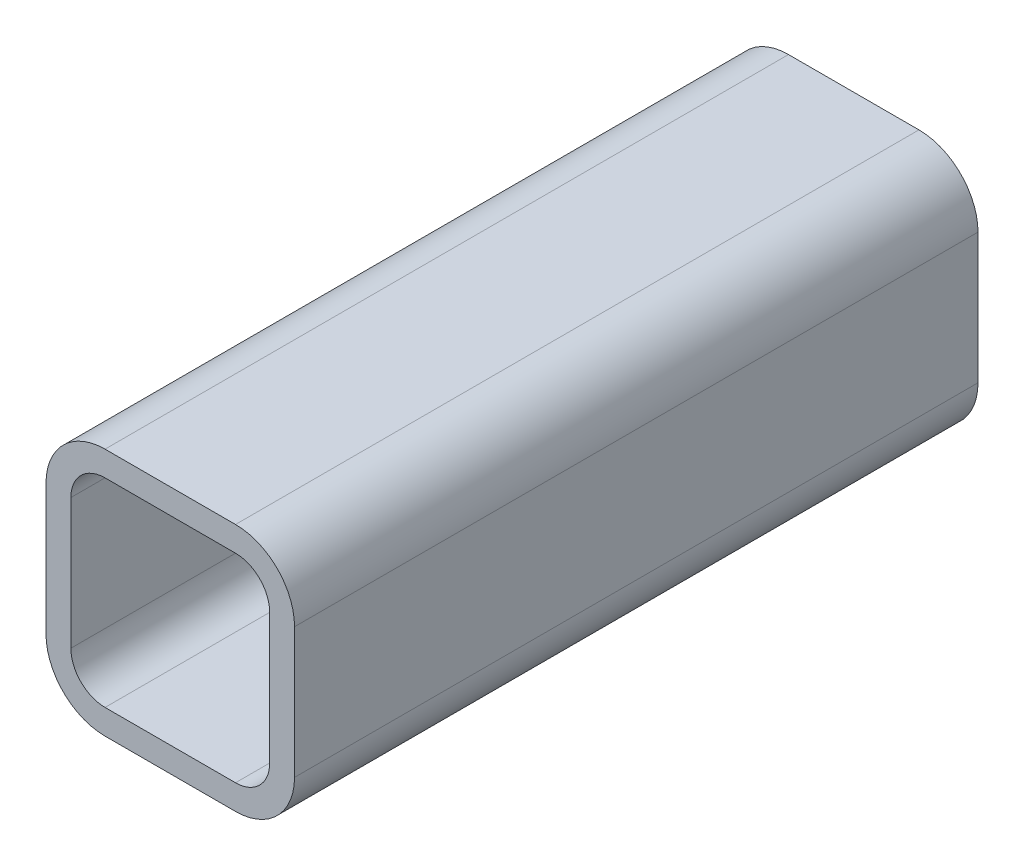
SolidWorks part; units mm, degrees
material "Q355"
ref_plane "前视基准面" through (0, 0, 0) normal (0, 0, 1) x (1, 0, 0)
ref_plane "上视基准面" through (0, 0, 0) normal (0, 1, 0) x (1, 0, 0)
ref_plane "右视基准面" through (0, 0, 0) normal (1, 0, 0) x (0, 0, -1)
sketch "草图1" plane through (0, 0, 0) normal (0, 0, 1) x (1, 0, 0)
  line L5 (0, 0) -> (0, 73.118) construction
  line L13 (0, 0) -> (96.1876, 0) construction
  line L14 (-32, 21) -> (-32, -21)
  line L15 (-21, 40) -> (21, 40)
  line L16 (-40, 21) -> (-40, -21)
  line L17 (-21, -40) -> (21, -40)
  line L18 (40, 21) -> (40, -21)
  line L19 (-21, -32) -> (21, -32)
  line L20 (32, 21) -> (32, -21)
  line L21 (-21, 32) -> (21, 32)
  arc A8 (-40, -21) -> (-21, -40) centre (-21, -21) ccw
  arc A9 (21, -40) -> (40, -21) centre (21, -21) ccw
  arc A10 (40, 21) -> (21, 40) centre (21, 21) ccw
  arc A11 (-21, 40) -> (-40, 21) centre (-21, 21) ccw
  arc A12 (-32, -21) -> (-21, -32) centre (-21, -21) ccw
  arc A13 (21, -32) -> (32, -21) centre (21, -21) ccw
  arc A14 (32, 21) -> (21, 32) centre (21, 21) ccw
  arc A15 (-21, 32) -> (-32, 21) centre (-21, 21) ccw
  dimension "D3" = 40
  dimension "D1" = 19
  dimension "D2" = 80
  dimension "D4" = 40
  dimension "D5" = 80
  dimension "D6" = 8
extrude "凸台-拉伸1" add sketch "草图1" along normal mid plane 220 contours L14 A12 L19 A13 L20 A14 L21 A15
hole_wizard "M10x1.0 螺纹孔1" positions "草图3" profile "草图4" tap size "M10x1.0" standard "GB"
sketch "草图3" plane through (0, -40, 0) normal (0, -1, 0) x (-1, 0, 0)
  point P0 (0, 0)
sketch "草图4" plane through (0, -40, 0) normal (1, 0, 0) x (0, 0, -1)
  line L0 (0, 0) -> (0, 25.7039)
  line L1 (0, 25.7039) -> (4.5, 23)
  line L2 (4.5, 23) -> (4.5, 0)
  line L5 (4.5, 0) -> (0, 0)
  line L10 (0, 25.7039) -> (-4.5, 23) construction
  line L11 (0, -6.35) -> (0, 107.95) construction
  dimension "螺纹孔钻头直径" = 9
  dimension "螺纹孔钻头深度" = 23
  dimension "导头角度" = 118
cosmetic thread "孔螺蚊线1" parameters "D1"=8, "D2"=10
